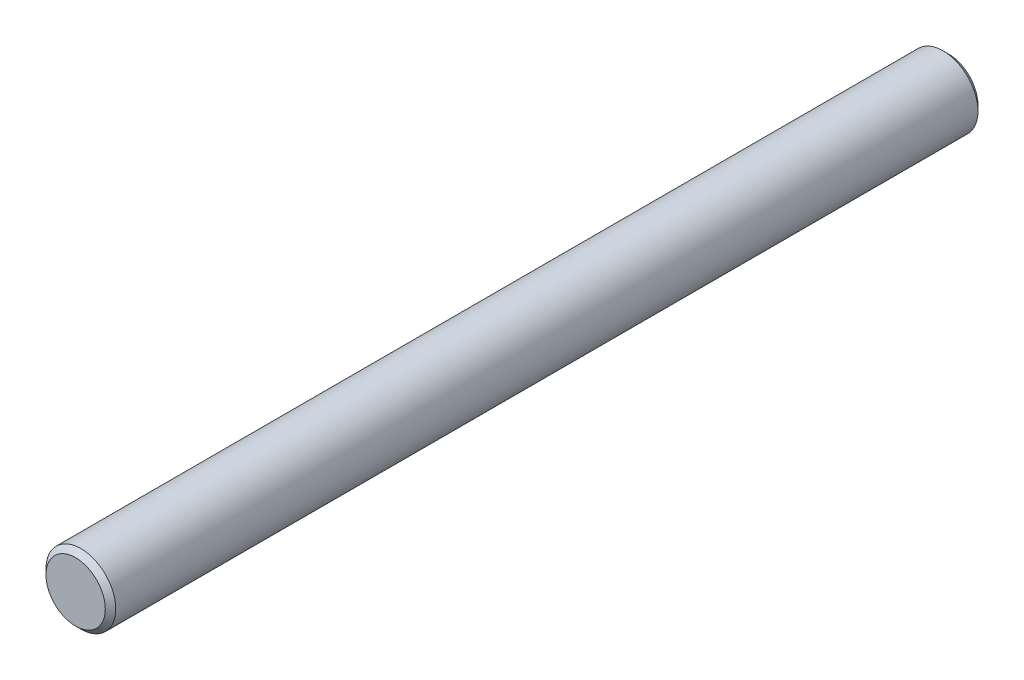
SolidWorks part; units mm, degrees
ref_plane "Front Plane" through (0, 0, 0) normal (0, 0, 1) x (1, 0, 0)
ref_plane "Top Plane" through (0, 0, 0) normal (0, 1, 0) x (1, 0, 0)
ref_plane "Right Plane" through (0, 0, 0) normal (1, 0, 0) x (0, 0, -1)
sketch "Sketch1" plane through (0, 0, 0) normal (0, 0, 1) x (1, 0, 0)
  line L0 (-4, 0) -> (4, 0) construction
  line L5 (0, 4) -> (0, -4) construction
  circle A1 centre (0, 0) radius 4
  point P7 (-4, 0)
  point P8 (4, 0)
  point P12 (0, -4)
  point P13 (0, 4)
  dimension "Diameter" = 8
sketch "Sketch2" plane through (0, 0, 0) normal (1, 0, 0) x (0, 0, -1)
  line L10 (-50, 0) -> (50, 0) construction
  line L11 (50, -4) -> (-50, -4)
  line L12 (50, -4) -> (50, 4)
  line L13 (50, 4) -> (-50, 4)
  line L14 (-50, -4) -> (-50, 4)
  line L15 (-40, 4) -> (-40, -4)
  line L16 (40, 4) -> (40, -4)
  line L17 (-40, 0) -> (40, 0) construction
  line L18 (-49.4, 4) -> (-50, 3.4) construction
  point P0 (0, 0)
  point P4 (0, 0)
  point P28 (0, 0)
  dimension "Chamfer Typ," = 45
  dimension "Length" = 100
  dimension "Chamfer Length" = 0.6
  dimension "D1" = 10
sketch "Sketch3" plane through (0, 0, 0) normal (0, 0, 1) x (1, 0, 0)
  circle A0 centre (0, 0) radius 4 construction
  circle A1 centre (0, 0) radius 4
extrude "Boss-Extrude1" add sketch "Sketch3" along normal up to vertex (50 mm away) and the other way up to vertex (50 mm away) other way up to point (0, 4, -50)
chamfer "Chamfer1" distance 0.6 angle 45 2 edges at (4, 0, -50) (4, 0, 50)
equation "\"D1@Chamfer1\"=\"Chamfer Length@Sketch2\""
equation "\"D2@Chamfer1\"=\"Chamfer Typ,@Sketch2\""
equation "\"Chamfer Length@Sketch2\" = \"Diameter@Sketch1\" * .075"
